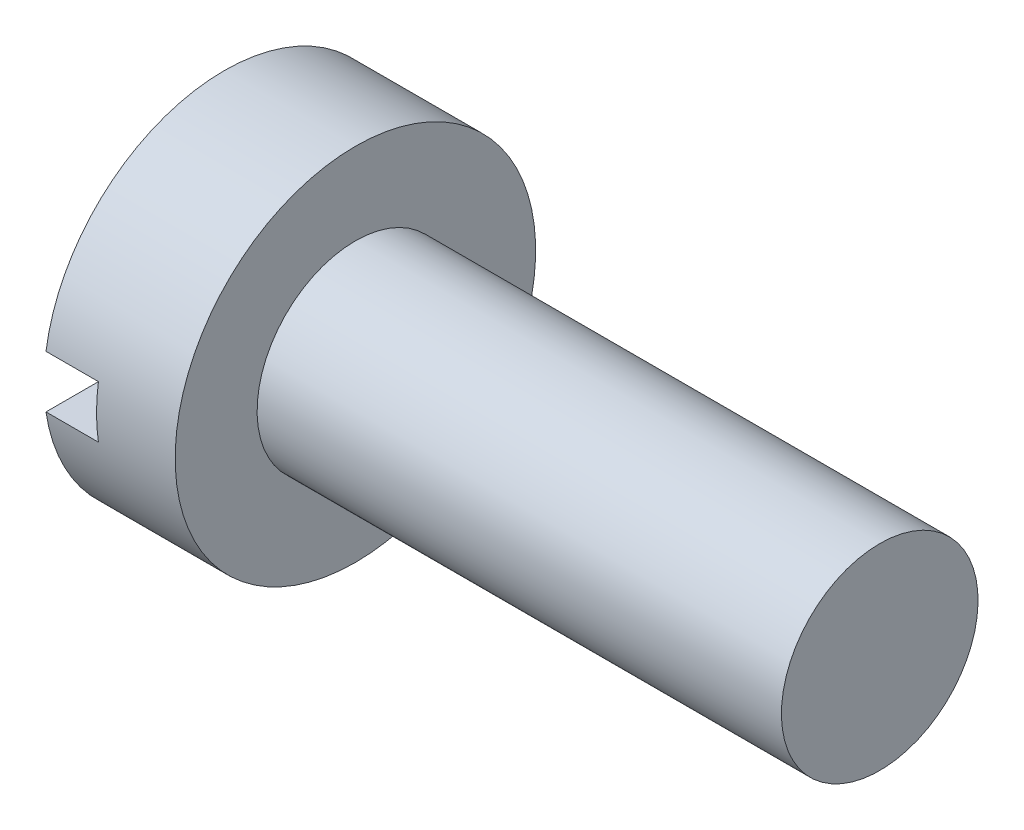
SolidWorks part; units mm, degrees
material "Plain Carbon Steel"
ref_plane "Front Plane" through (0, 0, 0) normal (0, 0, 1) x (1, 0, 0)
ref_plane "Top Plane" through (0, 0, 0) normal (0, 1, 0) x (1, 0, 0)
ref_plane "Right Plane" through (0, 0, 0) normal (1, 0, 0) x (0, 0, -1)
sketch "Sketch1" plane through (0, 0, 0) normal (0, 0, 1) x (1, 0, 0)
  line L0 (0, 0) -> (0, 2.75)
  line L1 (0, 2.75) -> (2, 2.75)
  line L2 (2, 2.75) -> (2, 1.5)
  line L3 (2, 1.5) -> (10, 1.5)
  line L4 (10, 1.5) -> (10, 0)
  line L5 (10, 0) -> (0, 0) construction
  line L6 (0, 0) -> (10, 0)
  dimension "D1" = 3
  dimension "D2" = 8
  dimension "D3" = 5.5
  dimension "D4" = 2
revolve "Revolve1" add sketch "Sketch1" angle 360 about L5
sketch "Sketch2" plane through (0, 0, 0) normal (-1, 0, 0) x (0, 0, 1)
  line L0 (2.75, 0) -> (-2.75, 0) construction
  line L1 (-2.75, 0.4) -> (2.75, 0.4)
  line L2 (-2.75, 0.4) -> (-2.75, -0.4)
  line L3 (-2.75, -0.4) -> (2.75, -0.4)
  line L4 (2.75, 0.4) -> (2.75, -0.4)
  circle A0 centre (0, 0) radius 2.75 construction
  dimension "D1" = 0.8
extrude "Cut-Extrude1" cut sketch "Sketch2" against normal blind 0.8
